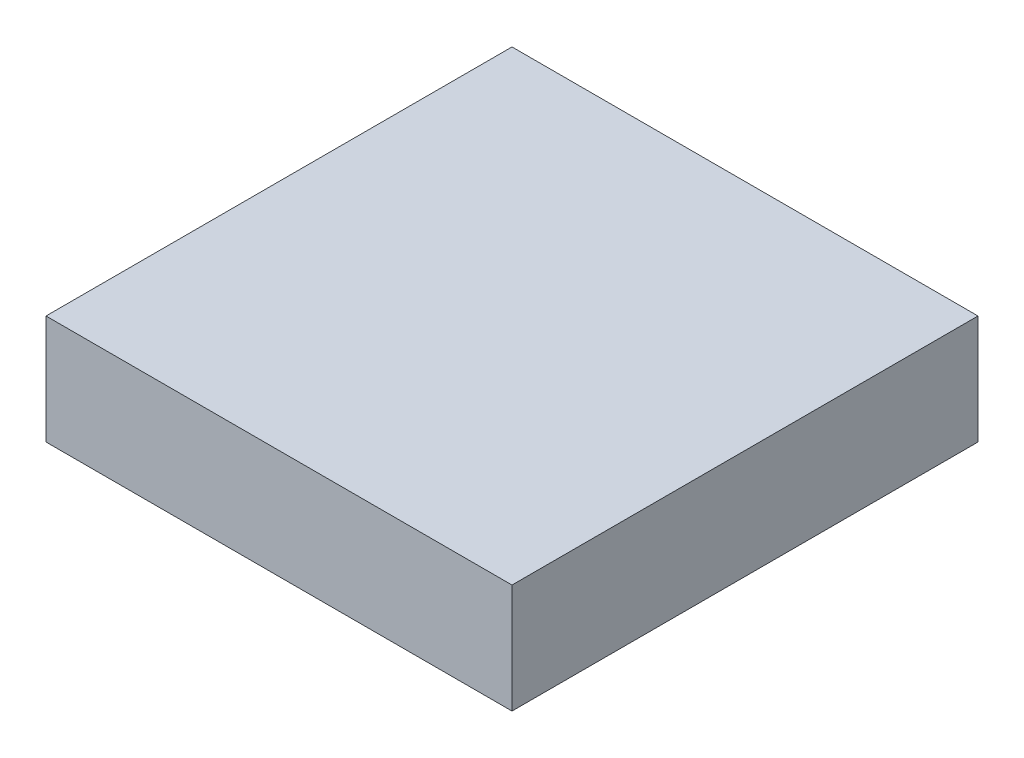
SolidWorks part; units mm, degrees
material "Mahogany"
ref_plane "Front Plane" through (0, 0, 0) normal (0, 0, 1) x (1, 0, 0)
ref_plane "Top Plane" through (0, 0, 0) normal (0, 1, 0) x (1, 0, 0)
ref_plane "Right Plane" through (0, 0, 0) normal (1, 0, 0) x (0, 0, -1)
sketch "Sketch1" plane through (0, 0, 0) normal (0, 1, 0) x (1, 0, 0)
  line L1 (-143, -143) -> (143, -143)
  line L2 (-143, -143) -> (-143, 143)
  line L3 (-143, 143) -> (143, 143)
  line L4 (143, -143) -> (143, 143)
  line L5 (-143, -143) -> (143, 143) construction
  line L6 (-143, 143) -> (143, -143) construction
  point P0 (0, 0)
  dimension "D1" = 286
  dimension "D2" = 286
extrude "Boss-Extrude1" add sketch "Sketch1" along normal blind 67
